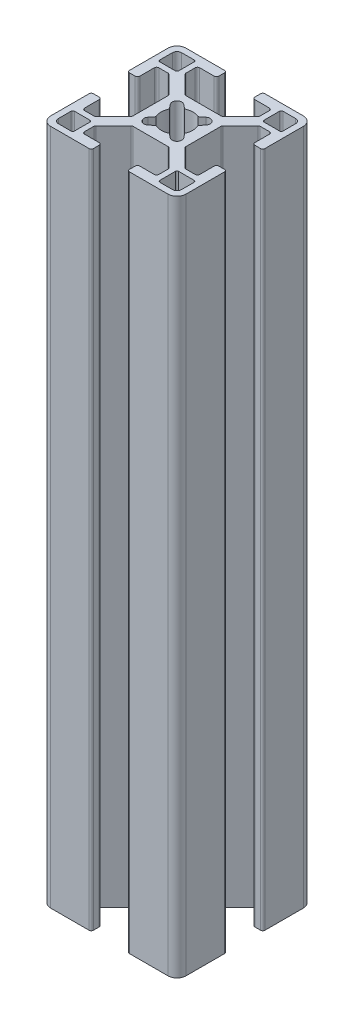
SolidWorks part; units mm, degrees
ref_plane "Front" through (0, 0, 0) normal (0, 0, 1) x (1, 0, 0)
ref_plane "Top" through (0, 0, 0) normal (0, 1, 0) x (1, 0, 0)
ref_plane "Right" through (0, 0, 0) normal (1, 0, 0) x (0, 0, -1)
sketch3d "3DSketch1"
  line L0 (0, 0, 0) -> (0, 150, 0)
  dimension "D1" = 150
other "Perfil com. aluminio PERFIL COMER. 30 X 30(1)"
ref_plane "Plano1" through (0, 0, 0) normal (0, 1, 0) x (1, 0, 0)
sketch "Esboço1" plane through (0, 0, 0) normal (0, 1, 0) x (1, 0, 0)
  line L10 (-3.1849, 1.488) -> (-3.9634, 2.4631)
  line L11 (-2.4631, 3.9634) -> (-1.488, 3.1849)
  line L16 (-9.46, 13.26) -> (-9.46, 9.84)
  line L17 (-9.84, 9.46) -> (-13.26, 9.46)
  line L18 (-13.64, 9.84) -> (-13.64, 12.64)
  line L19 (-12.64, 13.64) -> (-9.84, 13.64)
  line L44 (0, 5.8727) -> (-3.8729, 5.8727)
  line L45 (-4.2264, 6.0192) -> (-8.0736, 9.8663)
  line L46 (-8.22, 10.2198) -> (-8.22, 12.25)
  line L47 (-7.72, 12.75) -> (-4.5, 12.75)
  line L48 (-4, 13.25) -> (-4, 14.5)
  line L49 (-4.5, 15) -> (-13, 15)
  line L50 (-15, 13) -> (-15, 4.5)
  line L51 (-14.5, 4) -> (-13.25, 4)
  line L52 (-12.75, 4.5) -> (-12.75, 7.72)
  line L53 (-12.25, 8.22) -> (-10.2198, 8.22)
  line L54 (-9.8663, 8.0736) -> (-6.0192, 4.2264)
  line L55 (-5.8727, 3.8729) -> (-5.8727, 0)
  line L84 (13.64, 12.64) -> (13.64, 9.84)
  line L91 (15, 4.5) -> (15, 13)
  line L92 (13, 15) -> (4.5, 15)
  line L93 (4, 14.5) -> (4, 13.25)
  line L94 (4.5, 12.75) -> (7.72, 12.75)
  line L95 (8.22, 12.25) -> (8.22, 10.2198)
  line L96 (8.0736, 9.8663) -> (4.2264, 6.0192)
  line L97 (3.8729, 5.8727) -> (0, 5.8727)
  line L98 (1.488, 3.1849) -> (2.4631, 3.9634)
  line L99 (3.9634, 2.4631) -> (3.1849, 1.488)
  line L100 (5.8727, 0) -> (5.8727, 3.8729)
  line L101 (6.0192, 4.2264) -> (9.8663, 8.0736)
  line L102 (10.2198, 8.22) -> (12.25, 8.22)
  line L103 (12.75, 7.72) -> (12.75, 4.5)
  line L104 (13.25, 4) -> (14.5, 4)
  line L105 (13.26, 9.46) -> (9.84, 9.46)
  line L112 (9.46, 9.84) -> (9.46, 13.26)
  line L113 (9.84, 13.64) -> (12.64, 13.64)
  line L114 (12.64, -13.64) -> (9.84, -13.64)
  line L115 (4.5, -15) -> (13, -15)
  line L116 (15, -13) -> (15, -4.5)
  line L117 (14.5, -4) -> (13.25, -4)
  line L118 (12.75, -4.5) -> (12.75, -7.72)
  line L119 (12.25, -8.22) -> (10.2198, -8.22)
  line L120 (9.8663, -8.0736) -> (6.0192, -4.2264)
  line L121 (5.8727, -3.8729) -> (5.8727, 0)
  line L122 (3.1849, -1.488) -> (3.9634, -2.4631)
  line L123 (2.4631, -3.9634) -> (1.488, -3.1849)
  line L124 (0, -5.8727) -> (3.8729, -5.8727)
  line L125 (4.2264, -6.0192) -> (8.0736, -9.8663)
  line L126 (8.22, -10.2198) -> (8.22, -12.25)
  line L133 (7.72, -12.75) -> (4.5, -12.75)
  line L134 (4, -13.25) -> (4, -14.5)
  line L135 (9.46, -13.26) -> (9.46, -9.84)
  line L136 (9.84, -9.46) -> (13.26, -9.46)
  line L137 (13.64, -9.84) -> (13.64, -12.64)
  line L138 (-13.64, -12.64) -> (-13.64, -9.84)
  line L139 (-15, -4.5) -> (-15, -13)
  line L140 (-13, -15) -> (-4.5, -15)
  line L141 (-4, -14.5) -> (-4, -13.25)
  line L142 (-4.5, -12.75) -> (-7.72, -12.75)
  line L143 (-8.22, -12.25) -> (-8.22, -10.2198)
  line L144 (-8.0736, -9.8663) -> (-4.2264, -6.0192)
  line L145 (-3.8729, -5.8727) -> (0, -5.8727)
  line L146 (-1.488, -3.1849) -> (-2.4631, -3.9634)
  line L147 (-3.9634, -2.4631) -> (-3.1849, -1.488)
  line L148 (3.9634, 2.4631) -> (3.1849, 1.488) [skipped]
  line L149 (13.26, 9.46) -> (9.84, 9.46) [skipped]
  line L150 (9.46, 9.84) -> (9.46, 13.26) [skipped]
  line L151 (9.84, 13.64) -> (12.64, 13.64) [skipped]
  line L152 (13.64, 12.64) -> (13.64, 9.84) [skipped]
  line L153 (5.8727, 0) -> (5.8727, 3.8729) [skipped]
  line L154 (6.0192, 4.2264) -> (9.8663, 8.0736) [skipped]
  line L155 (10.2198, 8.22) -> (12.25, 8.22) [skipped]
  line L156 (12.75, 7.72) -> (12.75, 4.5) [skipped]
  line L157 (13.25, 4) -> (14.5, 4) [skipped]
  line L158 (15, 4.5) -> (15, 13) [skipped]
  line L159 (13, 15) -> (4.5, 15) [skipped]
  line L160 (4, 14.5) -> (4, 13.25) [skipped]
  line L161 (4.5, 12.75) -> (7.72, 12.75) [skipped]
  line L162 (8.22, 12.25) -> (8.22, 10.2198) [skipped]
  line L163 (8.0736, 9.8663) -> (4.2264, 6.0192) [skipped]
  line L164 (3.8729, 5.8727) -> (0, 5.8727) [skipped]
  line L165 (3.1849, -1.488) -> (3.9634, -2.4631) [skipped]
  line L166 (9.46, -13.26) -> (9.46, -9.84) [skipped]
  line L167 (9.84, -9.46) -> (13.26, -9.46) [skipped]
  line L168 (13.64, -9.84) -> (13.64, -12.64) [skipped]
  line L169 (12.64, -13.64) -> (9.84, -13.64) [skipped]
  line L170 (0, -5.8727) -> (3.8729, -5.8727) [skipped]
  line L171 (4.2264, -6.0192) -> (8.0736, -9.8663) [skipped]
  line L172 (8.22, -10.2198) -> (8.22, -12.25) [skipped]
  line L173 (7.72, -12.75) -> (4.5, -12.75) [skipped]
  line L174 (4, -13.25) -> (4, -14.5) [skipped]
  line L175 (4.5, -15) -> (13, -15) [skipped]
  line L176 (15, -13) -> (15, -4.5) [skipped]
  line L177 (14.5, -4) -> (13.25, -4) [skipped]
  line L178 (12.75, -4.5) -> (12.75, -7.72) [skipped]
  line L179 (12.25, -8.22) -> (10.2198, -8.22) [skipped]
  line L180 (9.8663, -8.0736) -> (6.0192, -4.2264) [skipped]
  line L181 (5.8727, -3.8729) -> (5.8727, 0) [skipped]
  line L182 (-9.46, -9.84) -> (-9.46, -13.26) [skipped]
  line L183 (-9.84, -13.64) -> (-12.64, -13.64) [skipped]
  line L184 (-13.64, -12.64) -> (-13.64, -9.84) [skipped]
  line L185 (-15, -4.5) -> (-15, -13) [skipped]
  line L186 (-13, -15) -> (-4.5, -15) [skipped]
  line L187 (-4, -14.5) -> (-4, -13.25) [skipped]
  line L188 (-4.5, -12.75) -> (-7.72, -12.75) [skipped]
  line L189 (-8.22, -12.25) -> (-8.22, -10.2198) [skipped]
  line L190 (2.4631, -3.9634) -> (1.488, -3.1849) [skipped]
  line L191 (-1.488, -3.1849) -> (-2.4631, -3.9634) [skipped]
  line L192 (-13.26, -9.46) -> (-9.84, -9.46) [skipped]
  line L193 (-6.0192, -4.2264) -> (-9.8663, -8.0736) [skipped]
  line L194 (-10.2198, -8.22) -> (-12.25, -8.22) [skipped]
  line L195 (-12.75, -7.72) -> (-12.75, -4.5) [skipped]
  line L196 (-13.25, -4) -> (-14.5, -4) [skipped]
  line L197 (-8.0736, -9.8663) -> (-4.2264, -6.0192) [skipped]
  line L198 (-3.8729, -5.8727) -> (0, -5.8727) [skipped]
  line L199 (1.488, 3.1849) -> (2.4631, 3.9634) [skipped]
  line L200 (-3.9634, -2.4631) -> (-3.1849, -1.488) [skipped]
  line L201 (-5.8727, 0) -> (-5.8727, -3.8729) [skipped]
  line L202 (-5.8727, 0) -> (-5.8727, -3.8729)
  line L203 (-6.0192, -4.2264) -> (-9.8663, -8.0736)
  line L204 (-10.2198, -8.22) -> (-12.25, -8.22)
  line L205 (-12.75, -7.72) -> (-12.75, -4.5)
  line L206 (-13.25, -4) -> (-14.5, -4)
  line L207 (-13.26, -9.46) -> (-9.84, -9.46)
  line L208 (-9.46, -9.84) -> (-9.46, -13.26)
  line L209 (-9.84, -13.64) -> (-12.64, -13.64)
  arc A10 (-3.1849, 1.488) -> (-3.5154, 0) centre (0, 0) ccw
  arc A11 (-2.4631, 3.9634) -> (-3.9634, 2.4631) centre (-3.1292, 3.1292) ccw
  arc A12 (0, 3.5154) -> (-1.488, 3.1849) centre (0, 0) ccw
  arc A16 (-9.46, 13.26) -> (-9.84, 13.64) centre (-9.84, 13.26) ccw
  arc A17 (-9.84, 9.46) -> (-9.46, 9.84) centre (-9.84, 9.84) ccw
  arc A18 (-13.64, 9.84) -> (-13.26, 9.46) centre (-13.26, 9.84) ccw
  arc A19 (-12.64, 13.64) -> (-13.64, 12.64) centre (-12.64, 12.64) ccw
  arc A41 (-7.72, 12.75) -> (-8.22, 12.25) centre (-7.72, 12.25) ccw
  arc A42 (-4.5, 12.75) -> (-4, 13.25) centre (-4.5, 13.25) ccw
  arc A43 (-4, 14.5) -> (-4.5, 15) centre (-4.5, 14.5) ccw
  arc A44 (-13, 15) -> (-15, 13) centre (-13, 13) ccw
  arc A45 (-15, 4.5) -> (-14.5, 4) centre (-14.5, 4.5) ccw
  arc A46 (-13.25, 4) -> (-12.75, 4.5) centre (-13.25, 4.5) ccw
  arc A47 (-12.25, 8.22) -> (-12.75, 7.72) centre (-12.25, 7.72) ccw
  arc A50 (-6.0192, 4.2264) -> (-5.8727, 3.8729) centre (-6.3727, 3.8729) cw
  arc A51 (-4.2264, 6.0192) -> (-3.8729, 5.8727) centre (-3.8729, 6.3727) ccw
  arc A52 (-8.22, 10.2198) -> (-8.0736, 9.8663) centre (-7.72, 10.2198) ccw
  arc A53 (-10.2198, 8.22) -> (-9.8663, 8.0736) centre (-10.2198, 7.72) cw
  arc A68 (15, 13) -> (13, 15) centre (13, 13) ccw
  arc A69 (13.64, 12.64) -> (12.64, 13.64) centre (12.64, 12.64) ccw
  arc A70 (4.5, 15) -> (4, 14.5) centre (4.5, 14.5) ccw
  arc A71 (4, 13.25) -> (4.5, 12.75) centre (4.5, 13.25) ccw
  arc A79 (8.22, 12.25) -> (7.72, 12.75) centre (7.72, 12.25) ccw
  arc A80 (8.22, 10.2198) -> (8.0736, 9.8663) centre (7.72, 10.2198) cw
  arc A81 (4.2264, 6.0192) -> (3.8729, 5.8727) centre (3.8729, 6.3727) cw
  arc A82 (1.488, 3.1849) -> (0, 3.5154) centre (0, 0) ccw
  arc A83 (3.9634, 2.4631) -> (2.4631, 3.9634) centre (3.1292, 3.1292) ccw
  arc A84 (3.5154, 0) -> (3.1849, 1.488) centre (0, 0) ccw
  arc A85 (6.0192, 4.2264) -> (5.8727, 3.8729) centre (6.3727, 3.8729) ccw
  arc A86 (10.2198, 8.22) -> (9.8663, 8.0736) centre (10.2198, 7.72) ccw
  arc A87 (12.75, 7.72) -> (12.25, 8.22) centre (12.25, 7.72) ccw
  arc A88 (12.75, 4.5) -> (13.25, 4) centre (13.25, 4.5) ccw
  arc A89 (14.5, 4) -> (15, 4.5) centre (14.5, 4.5) ccw
  arc A97 (13.26, 9.46) -> (13.64, 9.84) centre (13.26, 9.84) ccw
  arc A98 (9.46, 9.84) -> (9.84, 9.46) centre (9.84, 9.84) ccw
  arc A99 (9.84, 13.64) -> (9.46, 13.26) centre (9.84, 13.26) ccw
  arc A100 (13, -15) -> (15, -13) centre (13, -13) ccw
  arc A101 (12.64, -13.64) -> (13.64, -12.64) centre (12.64, -12.64) ccw
  arc A102 (15, -4.5) -> (14.5, -4) centre (14.5, -4.5) ccw
  arc A103 (13.25, -4) -> (12.75, -4.5) centre (13.25, -4.5) ccw
  arc A104 (12.25, -8.22) -> (12.75, -7.72) centre (12.25, -7.72) ccw
  arc A105 (10.2198, -8.22) -> (9.8663, -8.0736) centre (10.2198, -7.72) cw
  arc A106 (6.0192, -4.2264) -> (5.8727, -3.8729) centre (6.3727, -3.8729) cw
  arc A107 (3.1849, -1.488) -> (3.5154, 0) centre (0, 0) ccw
  arc A108 (3.9634, 2.4631) -> (2.4631, 3.9634) centre (3.1292, 3.1292) ccw [skipped]
  arc A109 (13.26, 9.46) -> (13.64, 9.84) centre (13.26, 9.84) ccw [skipped]
  arc A110 (9.46, 9.84) -> (9.84, 9.46) centre (9.84, 9.84) ccw [skipped]
  arc A111 (9.84, 13.64) -> (9.46, 13.26) centre (9.84, 13.26) ccw [skipped]
  arc A112 (13.64, 12.64) -> (12.64, 13.64) centre (12.64, 12.64) ccw [skipped]
  arc A113 (12.75, 7.72) -> (12.25, 8.22) centre (12.25, 7.72) ccw [skipped]
  arc A114 (12.75, 4.5) -> (13.25, 4) centre (13.25, 4.5) ccw [skipped]
  arc A115 (14.5, 4) -> (15, 4.5) centre (14.5, 4.5) ccw [skipped]
  arc A116 (15, 13) -> (13, 15) centre (13, 13) ccw [skipped]
  arc A117 (4.5, 15) -> (4, 14.5) centre (4.5, 14.5) ccw [skipped]
  arc A118 (4, 13.25) -> (4.5, 12.75) centre (4.5, 13.25) ccw [skipped]
  arc A119 (8.22, 12.25) -> (7.72, 12.75) centre (7.72, 12.25) ccw [skipped]
  arc A120 (4.2264, 6.0192) -> (3.8729, 5.8727) centre (3.8729, 6.3727) cw [skipped]
  arc A121 (6.0192, 4.2264) -> (5.8727, 3.8729) centre (6.3727, 3.8729) ccw [skipped]
  arc A122 (10.2198, 8.22) -> (9.8663, 8.0736) centre (10.2198, 7.72) ccw [skipped]
  arc A123 (8.22, 10.2198) -> (8.0736, 9.8663) centre (7.72, 10.2198) cw [skipped]
  arc A124 (2.4631, -3.9634) -> (3.9634, -2.4631) centre (3.1292, -3.1292) ccw [skipped]
  arc A125 (9.46, -13.26) -> (9.84, -13.64) centre (9.84, -13.26) ccw [skipped]
  arc A126 (9.84, -9.46) -> (9.46, -9.84) centre (9.84, -9.84) ccw [skipped]
  arc A127 (13.64, -9.84) -> (13.26, -9.46) centre (13.26, -9.84) ccw [skipped]
  arc A128 (12.64, -13.64) -> (13.64, -12.64) centre (12.64, -12.64) ccw [skipped]
  arc A129 (7.72, -12.75) -> (8.22, -12.25) centre (7.72, -12.25) ccw [skipped]
  arc A130 (4.5, -12.75) -> (4, -13.25) centre (4.5, -13.25) ccw [skipped]
  arc A131 (4, -14.5) -> (4.5, -15) centre (4.5, -14.5) ccw [skipped]
  arc A132 (13, -15) -> (15, -13) centre (13, -13) ccw [skipped]
  arc A133 (15, -4.5) -> (14.5, -4) centre (14.5, -4.5) ccw [skipped]
  arc A134 (13.25, -4) -> (12.75, -4.5) centre (13.25, -4.5) ccw [skipped]
  arc A135 (12.25, -8.22) -> (12.75, -7.72) centre (12.25, -7.72) ccw [skipped]
  arc A136 (6.0192, -4.2264) -> (5.8727, -3.8729) centre (6.3727, -3.8729) cw [skipped]
  arc A137 (4.2264, -6.0192) -> (3.8729, -5.8727) centre (3.8729, -6.3727) ccw [skipped]
  arc A138 (8.22, -10.2198) -> (8.0736, -9.8663) centre (7.72, -10.2198) ccw [skipped]
  arc A139 (10.2198, -8.22) -> (9.8663, -8.0736) centre (10.2198, -7.72) cw [skipped]
  arc A140 (-9.84, -13.64) -> (-9.46, -13.26) centre (-9.84, -13.26) ccw [skipped]
  arc A141 (-13.64, -12.64) -> (-12.64, -13.64) centre (-12.64, -12.64) ccw [skipped]
  arc A142 (-15, -13) -> (-13, -15) centre (-13, -13) ccw [skipped]
  arc A143 (-4.5, -15) -> (-4, -14.5) centre (-4.5, -14.5) ccw [skipped]
  arc A144 (-4, -13.25) -> (-4.5, -12.75) centre (-4.5, -13.25) ccw [skipped]
  arc A145 (-8.22, -12.25) -> (-7.72, -12.75) centre (-7.72, -12.25) ccw [skipped]
  arc A146 (0, -3.5154) -> (1.488, -3.1849) centre (0, 0) ccw [skipped]
  arc A147 (-1.488, -3.1849) -> (0, -3.5154) centre (0, 0) ccw [skipped]
  arc A148 (-3.9634, -2.4631) -> (-2.4631, -3.9634) centre (-3.1292, -3.1292) ccw [skipped]
  arc A149 (-13.26, -9.46) -> (-13.64, -9.84) centre (-13.26, -9.84) ccw [skipped]
  arc A150 (-9.46, -9.84) -> (-9.84, -9.46) centre (-9.84, -9.84) ccw [skipped]
  arc A151 (-12.75, -7.72) -> (-12.25, -8.22) centre (-12.25, -7.72) ccw [skipped]
  arc A152 (-12.75, -4.5) -> (-13.25, -4) centre (-13.25, -4.5) ccw [skipped]
  arc A153 (-14.5, -4) -> (-15, -4.5) centre (-14.5, -4.5) ccw [skipped]
  arc A154 (-4.2264, -6.0192) -> (-3.8729, -5.8727) centre (-3.8729, -6.3727) cw [skipped]
  arc A155 (-6.0192, -4.2264) -> (-5.8727, -3.8729) centre (-6.3727, -3.8729) ccw [skipped]
  arc A156 (-10.2198, -8.22) -> (-9.8663, -8.0736) centre (-10.2198, -7.72) ccw [skipped]
  arc A157 (-8.22, -10.2198) -> (-8.0736, -9.8663) centre (-7.72, -10.2198) cw [skipped]
  arc A158 (3.5154, 0) -> (3.1849, 1.488) centre (0, 0) ccw [skipped]
  arc A159 (3.1849, -1.488) -> (3.5154, 0) centre (0, 0) ccw [skipped]
  arc A160 (1.488, 3.1849) -> (0, 3.5154) centre (0, 0) ccw [skipped]
  arc A161 (-3.5154, 0) -> (-3.1849, -1.488) centre (0, 0) ccw [skipped]
  arc A162 (2.4631, -3.9634) -> (3.9634, -2.4631) centre (3.1292, -3.1292) ccw
  arc A163 (0, -3.5154) -> (1.488, -3.1849) centre (0, 0) ccw
  arc A164 (4.2264, -6.0192) -> (3.8729, -5.8727) centre (3.8729, -6.3727) ccw
  arc A165 (8.22, -10.2198) -> (8.0736, -9.8663) centre (7.72, -10.2198) ccw
  arc A166 (7.72, -12.75) -> (8.22, -12.25) centre (7.72, -12.25) ccw
  arc A167 (4.5, -12.75) -> (4, -13.25) centre (4.5, -13.25) ccw
  arc A168 (4, -14.5) -> (4.5, -15) centre (4.5, -14.5) ccw
  arc A169 (9.46, -13.26) -> (9.84, -13.64) centre (9.84, -13.26) ccw
  arc A170 (9.84, -9.46) -> (9.46, -9.84) centre (9.84, -9.84) ccw
  arc A171 (13.64, -9.84) -> (13.26, -9.46) centre (13.26, -9.84) ccw
  arc A172 (-15, -13) -> (-13, -15) centre (-13, -13) ccw
  arc A173 (-13.64, -12.64) -> (-12.64, -13.64) centre (-12.64, -12.64) ccw
  arc A174 (-4.5, -15) -> (-4, -14.5) centre (-4.5, -14.5) ccw
  arc A175 (-4, -13.25) -> (-4.5, -12.75) centre (-4.5, -13.25) ccw
  arc A176 (-8.22, -12.25) -> (-7.72, -12.75) centre (-7.72, -12.25) ccw
  arc A177 (-8.22, -10.2198) -> (-8.0736, -9.8663) centre (-7.72, -10.2198) cw
  arc A178 (-4.2264, -6.0192) -> (-3.8729, -5.8727) centre (-3.8729, -6.3727) cw
  arc A179 (-1.488, -3.1849) -> (0, -3.5154) centre (0, 0) ccw
  arc A180 (-3.9634, -2.4631) -> (-2.4631, -3.9634) centre (-3.1292, -3.1292) ccw
  arc A181 (-3.5154, 0) -> (-3.1849, -1.488) centre (0, 0) ccw
  arc A182 (-6.0192, -4.2264) -> (-5.8727, -3.8729) centre (-6.3727, -3.8729) ccw
  arc A183 (-10.2198, -8.22) -> (-9.8663, -8.0736) centre (-10.2198, -7.72) ccw
  arc A184 (-12.75, -7.72) -> (-12.25, -8.22) centre (-12.25, -7.72) ccw
  arc A185 (-12.75, -4.5) -> (-13.25, -4) centre (-13.25, -4.5) ccw
  arc A186 (-14.5, -4) -> (-15, -4.5) centre (-14.5, -4.5) ccw
  arc A187 (-13.26, -9.46) -> (-13.64, -9.84) centre (-13.26, -9.84) ccw
  arc A188 (-9.46, -9.84) -> (-9.84, -9.46) centre (-9.84, -9.84) ccw
  arc A189 (-9.84, -13.64) -> (-9.46, -13.26) centre (-9.84, -13.26) ccw
  point P0 (-8.75, 15)
  point P9 (0, 0)
  point P12 (-4.08, 5.8727)
  point P15 (-8.22, 10.0127)
  point P18 (-10.0127, 8.22)
  point P93 (0, 0)
  point P171 (0, 0)
  point P221 (0, 0)
  point P232 (0, 0)
  point P233 (0, 0)
  point P450 (0, 0)
  dimension "D3" = 1.0675
  dimension "D6" = 1.36
  dimension "D9" = 0.38
  dimension "D10" = 1
  dimension "D11" = 2
  dimension "D17" = 135
  dimension "D18" = 1.24
  dimension "D25" = 3.5154
  dimension "D39" = 0.5
  dimension "D20" = 15
  dimension "D26" = 0.5
  dimension "D4" = 167.212
  dimension "D5" = 25.043
  dimension "D7" = 1.36
  dimension "D8" = 4.18
  dimension "D12" = 4.18
  dimension "D13" = 1.24
  dimension "D14" = 2.25
  dimension "D15" = 11
  dimension "D16" = 11
  dimension "D19" = 15
  dimension "D21" = 4.14
  dimension "D22" = 38.606
  dimension "D23" = 25.043
  dimension "D24" = 38.606
  dimension "D27" = 5.8727
  dimension "D28" = 4
  dimension "D29" = 1.2477
  dimension "D30" = 4
  dimension "D33" = 135
  dimension "D38" = 0.5
hole_wizard "Durchgangsloch für M51" positions "3DSketch2" profile "Esboço3" hole size "M5" standard "DIN" end condition through all
sketch3d "3DSketch2"
  line L0 (-3.8729, 150, 5.8727) -> (3.8729, 150, 5.8727) construction
  point P0 (0, 120, 5.8727)
  point P2 (0, 70, 5.8727)
  point P5 (0, 0, 0)
  point P8 (0, 150, 5.8727)
  point P9 (0, 0, 0)
  dimension "D1" = 30
  dimension "D2" = 50
sketch "Esboço3" plane through (0, 120, 5.8727) normal (1, 0, 0) x (0, -1, 0)
  line L0 (0, 0) -> (0, 20.8727)
  line L1 (0, 20.8727) -> (2.65, 20.8727)
  line L2 (2.65, 20.8727) -> (2.65, 0)
  line L5 (2.65, 0) -> (0, 0)
  line L11 (0, -6.35) -> (0, 107.95) construction
  dimension "Thru Hole Dia." = 5.3
  dimension "Thru Hole Depth" = 20.8727
